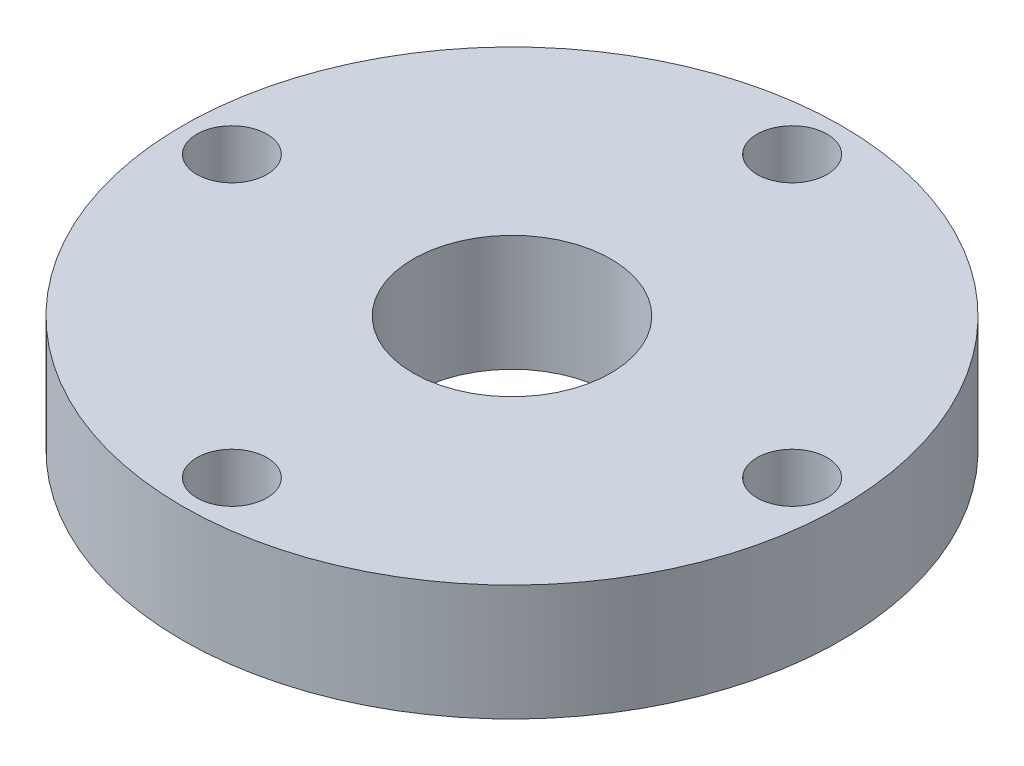
SolidWorks part; units mm, degrees
ref_plane "Front Plane" through (0, 0, 0) normal (1, 0, 0) x (0, 1, 0)
ref_plane "Top Plane" through (0, 0, 0) normal (0, 0, 1) x (0, 1, 0)
ref_plane "Right Plane" through (0, 0, 0) normal (0, 1, 0) x (-1, 0, 0)
sketch "Sketch1" plane through (0, 0, 0) normal (0, 0, 1) x (0, 1, 0)
  line L0 (-11.176, 0) -> (-11.176, 63.5)
  line L1 (-11.176, 63.5) -> (11.176, 63.5)
  line L2 (11.176, 63.5) -> (11.176, 0)
  line L3 (11.176, 0) -> (-11.176, 0)
  line L4 (-36.576, 0) -> (36.576, 0) construction
  point P6 (0, 0)
  dimension "D1" = 22.352
  dimension "D2" = 63.5
revolve "Revolve1" add sketch "Sketch1" angle 360 about L4
sketch "Sketch2" plane through (0, 0, 0) normal (0, 1, 0) x (-1, 0, 0)
  circle A0 centre (0, 0) radius 19.05
  point P2 (0, 0)
  dimension "D1" = 38.1
extrude "Cut-Extrude2" cut sketch "Sketch2" against normal through all from offset 11.176
hole_wizard "CBORE for 5/16 Socket Head Cap Screw1" positions "Sketch4" profile "Sketch3" counterbore size "5/16" standard "ANSI Inch"
sketch "Sketch4" plane through (0, 11.176, 0) normal (0, 1, 0) x (1, 0, 0)
  circle A0 centre (0, 0) radius 53.975 construction
  circle A1 centre (0, 0) radius 19.05 construction
  point P0 (-53.975, 0)
  point P1 (0, -53.975)
  point P3 (53.975, 0)
  point P5 (0, 53.975)
  dimension "D1" = 107.95
  dimension "D2" = 53.975
  dimension "D3" = 53.975
  dimension "D4" = 53.975
  dimension "D5" = 53.975
sketch "Sketch3" plane through (-53.975, 11.176, 0) normal (1, 0, 0) x (0, 0, 1)
  line L0 (0, 0) -> (0, 24.977)
  line L1 (0, 24.977) -> (4.3688, 22.352)
  line L2 (4.3688, 22.352) -> (4.3688, 9.652)
  line L3 (4.3688, 9.652) -> (6.7437, 9.652)
  line L4 (6.7437, 9.652) -> (6.7437, 0)
  line L5 (6.7437, 0) -> (0, 0)
  line L10 (0, 24.977) -> (-4.3688, 22.352) construction
  line L11 (0, -6.35) -> (0, 107.95) construction
  dimension "Hole Dia." = 8.7376
  dimension "Hole Depth" = 22.352
  dimension "C'Bore Dia." = 13.4874
  dimension "C'Bore Depth" = 9.652
  dimension "Drill Angle" = 118
